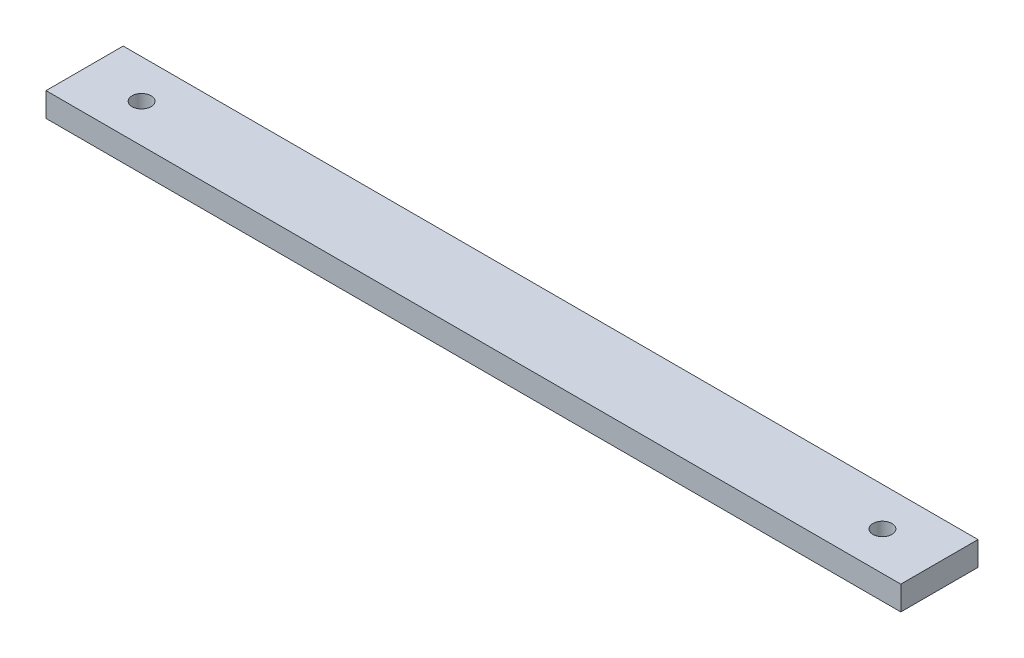
SolidWorks part; units mm, degrees
ref_plane "Front Plane" through (0, 0, 0) normal (0, 0, 1) x (1, 0, 0)
ref_plane "Top Plane" through (0, 0, 0) normal (0, 1, 0) x (1, 0, 0)
ref_plane "Right Plane" through (0, 0, 0) normal (1, 0, 0) x (0, 0, -1)
sketch "Sketch1" plane through (0, 0, 0) normal (0, 1, 0) x (1, 0, 0)
  line L0 (15, 10.16) -> (15, 20.32) construction
  line L1 (0, 0) -> (225, 0)
  line L2 (0, 0) -> (0, 20.32)
  line L3 (0, 20.32) -> (225, 20.32)
  line L4 (225, 0) -> (225, 20.32)
  line L5 (15, 10.16) -> (15, 0) construction
  line L6 (112.5, 20.32) -> (112.5, 0) construction
  circle A0 centre (15, 10.16) radius 2.5
  circle A1 centre (210, 10.16) radius 2.5
  dimension "D4" = 5
  dimension "D1" = 225
  dimension "D2" = 20.32
  dimension "D3" = 15
extrude "Boss-Extrude1" add sketch "Sketch1" along normal blind 6.35
